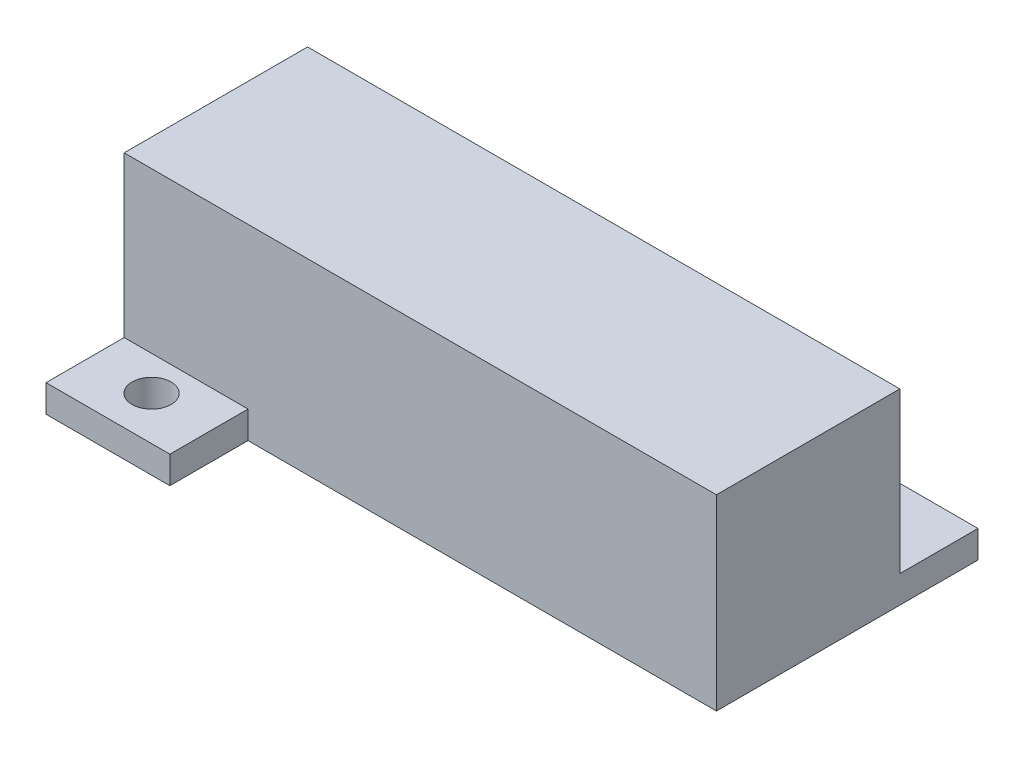
SolidWorks part; units mm, degrees
ref_plane "Front Plane" through (0, 0, 0) normal (0, 0, 1) x (1, 0, 0)
ref_plane "Top Plane" through (0, 0, 0) normal (0, 1, 0) x (1, 0, 0)
ref_plane "Right Plane" through (0, 0, 0) normal (1, 0, 0) x (0, 0, -1)
sketch "Sketch1" plane through (0, 0, 0) normal (0, 1, 0) x (1, 0, 0)
  line L0 (0, 0) -> (10.4648, 0)
  line L1 (10.4648, 0) -> (10.4648, 6.604)
  line L2 (10.4648, 6.604) -> (50.038, 6.604)
  line L3 (50.038, 6.604) -> (50.038, 28.702)
  line L4 (50.038, 28.702) -> (39.5732, 28.702)
  line L5 (39.5732, 28.702) -> (39.5732, 22.098)
  line L6 (39.5732, 22.098) -> (0, 22.098)
  line L7 (0, 22.098) -> (0, 0)
  line L8 (5.2324, 0) -> (5.2324, 22.098) construction
  line L9 (44.8056, 28.702) -> (44.8056, 6.604) construction
  circle A0 centre (5.2324, 3.683) radius 1.651
  circle A1 centre (44.8056, 25.019) radius 1.651
  point P17 (0, 0)
  dimension "D7" = 3.302
  dimension "D1" = 10.4648
  dimension "D2" = 10.4648
  dimension "D3" = 50.038
  dimension "D4" = 22.098
  dimension "D5" = 22.098
  dimension "D6" = 15.494
  dimension "D8" = 18.415
  dimension "D9" = 18.415
extrude "Boss-Extrude1" add sketch "Sketch1" along normal blind 2.3114
sketch "Sketch2" plane through (0, 2.3114, 0) normal (0, 1, 0) x (1, 0, 0)
  line L1 (50.038, 6.604) -> (0, 6.604)
  line L2 (50.038, 6.604) -> (50.038, 22.098)
  line L3 (50.038, 22.098) -> (0, 22.098)
  line L4 (0, 6.604) -> (0, 22.098)
extrude "Boss-Extrude2" add sketch "Sketch2" along normal blind 13.5128
ref_plane "Plane1" through (0, 0, -14.351) normal (0, 0, 1) x (1, 0, 0)
ref_plane "Plane2" through (5.2324, 0, 0) normal (1, 0, 0) x (0, 0, -1)
ref_plane "Plane3" through (44.8056, 0, 0) normal (1, 0, 0) x (0, 0, -1)
equation "\"D2@Sketch1\"=\"D1@Sketch1\""
equation "\"D5@Sketch1\"=\"D4@Sketch1\""
equation "\"D8@Sketch1\"=0.66in+\"D7@Sketch1\"/2"
equation "\"D9@Sketch1\"=\"D8@Sketch1\""
